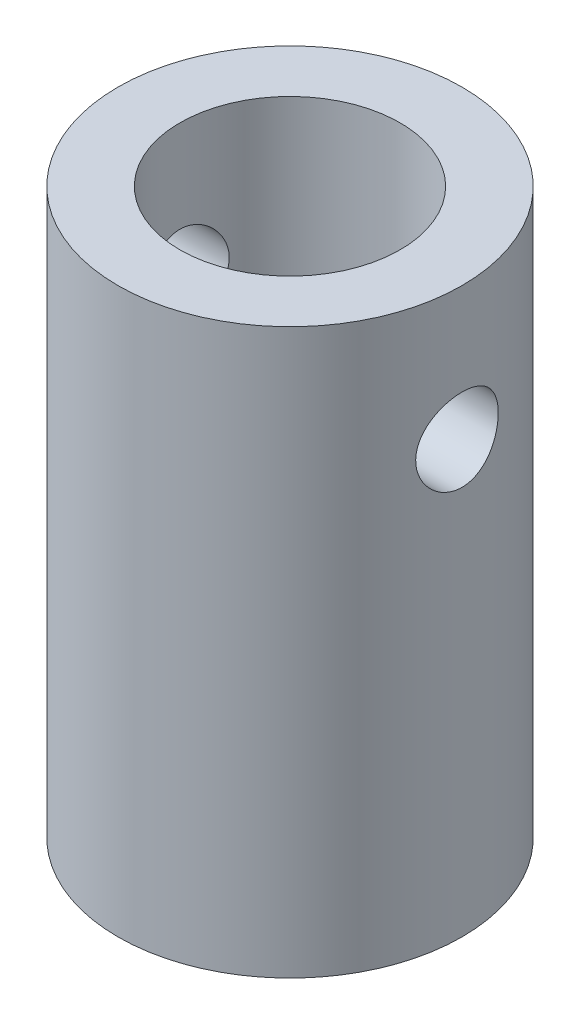
SolidWorks part; units mm, degrees
ref_plane "前视基准面" through (0, 0, 0) normal (0, 0, 1) x (1, 0, 0)
ref_plane "上视基准面" through (0, 0, 0) normal (0, 1, 0) x (1, 0, 0)
ref_plane "右视基准面" through (0, 0, 0) normal (1, 0, 0) x (0, 0, -1)
sketch "草图1" plane through (0, 0, 0) normal (0, 1, 0) x (1, 0, 0)
  circle A0 centre (0, 0) radius 12.5
  arc A1 (1.3201, 7.2813) -> (1.0368, 7.327) centre (0, 0) ccw
  arc A2 (-0.3333, 7.3925) -> (-0.6196, 7.374) centre (0, 0) ccw
  arc A3 (-1.9699, 7.133) -> (-2.2449, 7.0513) centre (0, 0) ccw
  arc A4 (-3.5077, 6.5158) -> (-3.7577, 6.3749) centre (0, 0) ccw
  arc A5 (-4.8697, 5.5719) -> (-5.082, 5.3789) centre (0, 0) ccw
  arc A6 (-5.9875, 4.3486) -> (-6.1516, 4.1132) centre (0, 0) ccw
  arc A7 (-6.805, 2.9072) -> (-6.9126, 2.6412) centre (0, 0) ccw
  arc A8 (-7.2813, 1.3201) -> (-7.327, 1.0368) centre (0, 0) ccw
  arc A9 (-7.3925, -0.3333) -> (-7.374, -0.6196) centre (0, 0) ccw
  arc A10 (-7.133, -1.9699) -> (-7.0513, -2.2449) centre (0, 0) ccw
  arc A11 (-6.5158, -3.5077) -> (-6.3749, -3.7577) centre (0, 0) ccw
  arc A12 (-5.5719, -4.8697) -> (-5.3789, -5.082) centre (0, 0) ccw
  arc A13 (-4.3486, -5.9875) -> (-4.1132, -6.1516) centre (0, 0) ccw
  arc A14 (-2.9072, -6.805) -> (-2.6412, -6.9126) centre (0, 0) ccw
  arc A15 (-1.3201, -7.2813) -> (-1.0368, -7.327) centre (0, 0) ccw
  arc A16 (0.3333, -7.3925) -> (0.6196, -7.374) centre (0, 0) ccw
  arc A17 (1.9699, -7.133) -> (2.2449, -7.0513) centre (0, 0) ccw
  arc A18 (3.5077, -6.5158) -> (3.7577, -6.3749) centre (0, 0) ccw
  arc A19 (4.8697, -5.5719) -> (5.082, -5.3789) centre (0, 0) ccw
  arc A20 (5.9875, -4.3486) -> (6.1516, -4.1132) centre (0, 0) ccw
  arc A21 (6.805, -2.9072) -> (6.9126, -2.6412) centre (0, 0) ccw
  arc A22 (7.2813, -1.3201) -> (7.327, -1.0368) centre (0, 0) ccw
  arc A23 (7.3925, 0.3333) -> (7.374, 0.6196) centre (0, 0) ccw
  arc A24 (7.133, 1.9699) -> (7.0513, 2.2449) centre (0, 0) ccw
  arc A25 (6.5158, 3.5077) -> (6.3749, 3.7577) centre (0, 0) ccw
  arc A26 (5.5719, 4.8697) -> (5.3789, 5.082) centre (0, 0) ccw
  arc A27 (4.3486, 5.9875) -> (4.1132, 6.1516) centre (0, 0) ccw
  arc A28 (2.9072, 6.805) -> (2.6412, 6.9126) centre (0, 0) ccw
  spline S0 degree 3 poles (1.0368, 7.327) (0.9813, 7.2702) (0.9257, 7.2132) (0.8222, 7.0949) (0.7743, 7.0337) (0.6353, 6.8476) (0.5489, 6.72) (0.4775, 6.5871) knots 0 0 0 0 0.25 0.25 0.5 0.5 1 1 1 1
  spline S1 degree 3 poles (0.1466, 6.5886) (0.0874, 6.7295) (0.0225, 6.869) (-0.0958, 7.0714) (-0.1389, 7.1376) (-0.2325, 7.2668) (-0.283, 7.3297) (-0.3333, 7.3925) knots 0 0 0 0 0.5 0.5 0.75 0.75 1 1 1 1
  spline S2 degree 3 poles (-0.6196, 7.374) (-0.661, 7.3063) (-0.7026, 7.2384) (-0.7771, 7.1) (-0.81, 7.0297) (-0.9045, 6.8175) (-0.9618, 6.6745) (-1.0018, 6.5291) knots 0 0 0 0 0.25 0.25 0.5 0.5 1 1 1 1
  spline S3 degree 3 poles (-1.3247, 6.457) (-1.4136, 6.581) (-1.5073, 6.7025) (-1.6673, 6.8732) (-1.724, 6.9281) (-1.8439, 7.033) (-1.907, 7.083) (-1.9699, 7.133) knots 0 0 0 0 0.5 0.5 0.75 0.75 1 1 1 1
  spline S4 degree 3 poles (-2.2449, 7.0513) (-2.2702, 6.9761) (-2.2957, 6.9007) (-2.3374, 6.7494) (-2.3537, 6.6736) (-2.3991, 6.446) (-2.4244, 6.2939) (-2.4311, 6.1434) knots 0 0 0 0 0.25 0.25 0.5 0.5 1 1 1 1
  spline S5 degree 3 poles (-2.7298, 6.0012) (-2.8439, 6.1021) (-2.9619, 6.1997) (-3.1556, 6.3303) (-3.223, 6.3711) (-3.3629, 6.4465) (-3.4355, 6.4812) (-3.5077, 6.5158) knots 0 0 0 0 0.5 0.5 0.75 0.75 1 1 1 1
  spline S6 degree 3 poles (-3.7577, 6.3749) (-3.7657, 6.2961) (-3.7737, 6.2171) (-3.7806, 6.0606) (-3.7796, 5.9832) (-3.7736, 5.7514) (-3.7656, 5.5973) (-3.7387, 5.4493) knots 0 0 0 0 0.25 0.25 0.5 0.5 1 1 1 1
  spline S7 degree 3 poles (-3.9983, 5.2442) (-4.1317, 5.3171) (-4.2683, 5.3857) (-4.4858, 5.4696) (-4.5605, 5.4943) (-4.7134, 5.5366) (-4.7917, 5.5543) (-4.8697, 5.5719) knots 0 0 0 0 0.5 0.5 0.75 0.75 1 1 1 1
  spline S8 degree 3 poles (-5.082, 5.3789) (-5.0723, 5.3005) (-5.0626, 5.2218) (-5.0345, 5.0679) (-5.0162, 4.9928) (-4.9592, 4.7685) (-4.9181, 4.6198) (-4.8591, 4.4817) knots 0 0 0 0 0.25 0.25 0.5 0.5 1 1 1 1
  spline S9 degree 3 poles (-5.0665, 4.2239) (-5.2125, 4.2652) (-5.3608, 4.3013) (-5.5912, 4.3343) (-5.6694, 4.3418) (-5.8275, 4.349) (-5.9076, 4.3488) (-5.9875, 4.3486) knots 0 0 0 0 0.5 0.5 0.75 0.75 1 1 1 1
  spline S10 degree 3 poles (-6.1516, 4.1132) (-6.1247, 4.039) (-6.0978, 3.9646) (-6.0362, 3.8211) (-6.0017, 3.7522) (-5.8966, 3.5463) (-5.8242, 3.4102) (-5.736, 3.289) knots 0 0 0 0 0.25 0.25 0.5 0.5 1 1 1 1
  spline S11 degree 3 poles (-5.8809, 2.9915) (-6.0321, 2.9993) (-6.1847, 3.0007) (-6.4163, 2.9813) (-6.494, 2.9713) (-6.6495, 2.9432) (-6.7273, 2.9251) (-6.805, 2.9072) knots 0 0 0 0 0.5 0.5 0.75 0.75 1 1 1 1
  spline S12 degree 3 poles (-6.9126, 2.6412) (-6.87, 2.575) (-6.8273, 2.5086) (-6.7355, 2.3826) (-6.6866, 2.3232) (-6.5388, 2.1461) (-6.4383, 2.0294) (-6.3256, 1.931) knots 0 0 0 0 0.25 0.25 0.5 0.5 1 1 1 1
  spline S13 degree 3 poles (-6.4007, 1.6088) (-6.5496, 1.5827) (-6.6983, 1.5492) (-6.9194, 1.4784) (-6.9928, 1.4515) (-7.1379, 1.3897) (-7.2097, 1.3548) (-7.2813, 1.3201) knots 0 0 0 0 0.5 0.5 0.75 0.75 1 1 1 1
  spline S14 degree 3 poles (-7.327, 1.0368) (-7.2708, 0.9818) (-7.2145, 0.9267) (-7.0973, 0.8245) (-7.0365, 0.7775) (-6.8533, 0.638) (-6.7297, 0.5467) (-6.5982, 0.476) knots 0 0 0 0 0.25 0.25 0.5 0.5 1 1 1 1
  spline S15 degree 3 poles (-6.5997, 0.1451) (-6.7389, 0.0866) (-6.8759, 0.0197) (-7.0753, -0.0988) (-7.1408, -0.1413) (-7.2684, -0.2336) (-7.3305, -0.2835) (-7.3925, -0.3333) knots 0 0 0 0 0.5 0.5 0.75 0.75 1 1 1 1
  spline S16 degree 3 poles (-7.374, -0.6196) (-7.3071, -0.6606) (-7.2401, -0.7018) (-7.1033, -0.7752) (-7.0338, -0.8075) (-6.8245, -0.9025) (-6.6839, -0.9637) (-6.5402, -1.0033) knots 0 0 0 0 0.25 0.25 0.5 0.5 1 1 1 1
  spline S17 degree 3 poles (-6.468, -1.3262) (-6.5906, -1.4141) (-6.7086, -1.511) (-6.8761, -1.6712) (-6.9305, -1.727) (-7.0343, -1.8452) (-7.0837, -1.9077) (-7.133, -1.9699) knots 0 0 0 0 0.5 0.5 0.75 0.75 1 1 1 1
  spline S18 degree 3 poles (-7.0513, -2.2449) (-6.9771, -2.27) (-6.9026, -2.2952) (-6.7532, -2.3363) (-6.6783, -2.3523) (-6.4535, -2.3982) (-6.3031, -2.426) (-6.1545, -2.4326) knots 0 0 0 0 0.25 0.25 0.5 0.5 1 1 1 1
  spline S19 degree 3 poles (-6.0123, -2.7313) (-6.1121, -2.8442) (-6.2045, -2.9661) (-6.3319, -3.1598) (-6.3725, -3.2261) (-6.4474, -3.3643) (-6.4816, -3.4361) (-6.5158, -3.5077) knots 0 0 0 0 0.5 0.5 0.75 0.75 1 1 1 1
  spline S20 degree 3 poles (-6.3749, -3.7577) (-6.2971, -3.7656) (-6.219, -3.7736) (-6.0644, -3.7805) (-5.9879, -3.7795) (-5.7589, -3.774) (-5.6066, -3.7668) (-5.4604, -3.7402) knots 0 0 0 0 0.25 0.25 0.5 0.5 1 1 1 1
  spline S21 degree 3 poles (-5.2553, -3.9998) (-5.3275, -4.132) (-5.3893, -4.2723) (-5.4699, -4.4897) (-5.4948, -4.5634) (-5.5372, -4.7146) (-5.5545, -4.7923) (-5.5719, -4.8697) knots 0 0 0 0 0.5 0.5 0.75 0.75 1 1 1 1
  spline S22 degree 3 poles (-5.3789, -5.082) (-5.3014, -5.0724) (-5.2236, -5.0628) (-5.0714, -5.0353) (-4.9971, -5.0174) (-4.7754, -4.9609) (-4.6292, -4.9189) (-4.4927, -4.8606) knots 0 0 0 0 0.25 0.25 0.5 0.5 1 1 1 1
  spline S23 degree 3 poles (-4.235, -5.068) (-4.276, -5.2131) (-4.3037, -5.3642) (-4.3335, -5.5943) (-4.3416, -5.6716) (-4.3493, -5.8285) (-4.3489, -5.9081) (-4.3486, -5.9875) knots 0 0 0 0 0.5 0.5 0.75 0.75 1 1 1 1
  spline S24 degree 3 poles (-4.1132, -6.1516) (-4.0398, -6.1249) (-3.9661, -6.0982) (-3.8239, -6.0376) (-3.7554, -6.0037) (-3.5522, -5.8991) (-3.42, -5.8247) (-3.3, -5.7375) knots 0 0 0 0 0.25 0.25 0.5 0.5 1 1 1 1
  spline S25 degree 3 poles (-3.0026, -5.8824) (-3.0103, -6.0331) (-3.0024, -6.1869) (-2.9799, -6.4181) (-2.9707, -6.4953) (-2.9434, -6.6501) (-2.9252, -6.7277) (-2.9072, -6.805) knots 0 0 0 0 0.5 0.5 0.75 0.75 1 1 1 1
  spline S26 degree 3 poles (-2.6412, -6.9126) (-2.5756, -6.8703) (-2.5097, -6.8279) (-2.3845, -6.7372) (-2.3251, -6.689) (-2.1506, -6.5415) (-2.0396, -6.4388) (-1.9421, -6.3271) knots 0 0 0 0 0.25 0.25 0.5 0.5 1 1 1 1
  spline S27 degree 3 poles (-1.6199, -6.4022) (-1.5938, -6.5509) (-1.5508, -6.6993) (-1.477, -6.9199) (-1.4509, -6.9932) (-1.3899, -7.1382) (-1.3549, -7.2098) (-1.3201, -7.2813) knots 0 0 0 0 0.5 0.5 0.75 0.75 1 1 1 1
  spline S28 degree 3 poles (-1.0368, -7.327) (-0.9823, -7.2711) (-0.9275, -7.2151) (-0.8256, -7.099) (-0.7783, -7.0389) (-0.6413, -6.856) (-0.5572, -6.7303) (-0.487, -6.5997) knots 0 0 0 0 0.25 0.25 0.5 0.5 1 1 1 1
  spline S29 degree 3 poles (-0.1562, -6.6012) (-0.0976, -6.7406) (-0.0218, -6.8757) (0.0996, -7.0746) (0.1414, -7.1403) (0.2332, -7.2683) (0.2833, -7.3305) (0.3333, -7.3925) knots 0 0 0 0 0.5 0.5 0.75 0.75 1 1 1 1
  spline S30 degree 3 poles (0.6196, -7.374) (0.6604, -7.3073) (0.7013, -7.2404) (0.7751, -7.1042) (0.8079, -7.035) (0.9004, -6.8261) (0.9528, -6.6847) (0.9922, -6.5417) knots 0 0 0 0 0.25 0.25 0.5 0.5 1 1 1 1
  spline S31 degree 3 poles (1.3151, -6.4695) (1.4034, -6.5927) (1.5079, -6.7074) (1.6709, -6.8745) (1.7263, -6.9295) (1.8445, -7.034) (1.9073, -7.0836) (1.9699, -7.133) knots 0 0 0 0 0.5 0.5 0.75 0.75 1 1 1 1
  spline S32 degree 3 poles (2.2449, -7.0513) (2.2699, -6.9771) (2.2949, -6.9027) (2.3366, -6.7533) (2.3534, -6.6784) (2.3966, -6.4539) (2.4149, -6.3044) (2.4215, -6.156) knots 0 0 0 0 0.25 0.25 0.5 0.5 1 1 1 1
  spline S33 degree 3 poles (2.7202, -6.0138) (2.834, -6.1144) (2.9617, -6.2031) (3.1582, -6.33) (3.2245, -6.3713) (3.3632, -6.4471) (3.4356, -6.4815) (3.5077, -6.5158) knots 0 0 0 0 0.5 0.5 0.75 0.75 1 1 1 1
  spline S34 degree 3 poles (3.7577, -6.3749) (3.7655, -6.2969) (3.7733, -6.2187) (3.7809, -6.0635) (3.7806, -5.9867) (3.7724, -5.7579) (3.7557, -5.6082) (3.7291, -5.4619) knots 0 0 0 0 0.25 0.25 0.5 0.5 1 1 1 1
  spline S35 degree 3 poles (3.9887, -5.2568) (4.1222, -5.3297) (4.2667, -5.388) (4.4868, -5.4683) (4.5608, -5.4939) (4.7132, -5.537) (4.7916, -5.5544) (4.8697, -5.5719) knots 0 0 0 0 0.5 0.5 0.75 0.75 1 1 1 1
  spline S36 degree 3 poles (5.082, -5.3789) (5.0722, -5.301) (5.0624, -5.2229) (5.0353, -5.0696) (5.0179, -4.9946) (4.9586, -4.7732) (4.9081, -4.6312) (4.8495, -4.4942) knots 0 0 0 0 0.25 0.25 0.5 0.5 1 1 1 1
  spline S37 degree 3 poles (5.0569, -4.2365) (5.2036, -4.278) (5.3575, -4.3032) (5.5903, -4.3328) (5.6684, -4.3413) (5.8268, -4.3494) (5.9073, -4.3489) (5.9875, -4.3486) knots 0 0 0 0 0.5 0.5 0.75 0.75 1 1 1 1
  spline S38 degree 3 poles (6.1516, -4.1132) (6.1246, -4.0393) (6.0976, -3.9652) (6.0369, -3.8215) (6.0033, -3.752) (5.8957, -3.5492) (5.8142, -3.4223) (5.7265, -3.3015) knots 0 0 0 0 0.25 0.25 0.5 0.5 1 1 1 1
  spline S39 degree 3 poles (5.8714, -3.0041) (6.0238, -3.0119) (6.1796, -3.0031) (6.4136, -2.9804) (6.4917, -2.9712) (6.6483, -2.9438) (6.7268, -2.9254) (6.805, -2.9072) knots 0 0 0 0 0.5 0.5 0.75 0.75 1 1 1 1
  spline S40 degree 3 poles (6.9126, -2.6412) (6.8698, -2.5751) (6.8269, -2.5087) (6.7355, -2.3818) (6.6872, -2.3215) (6.5368, -2.1475) (6.4287, -2.042) (6.316, -1.9436) knots 0 0 0 0 0.25 0.25 0.5 0.5 1 1 1 1
  spline S41 degree 3 poles (6.3911, -1.6214) (6.5417, -1.595) (6.6919, -1.5527) (6.9154, -1.4788) (6.9896, -1.4524) (7.1364, -1.3907) (7.2089, -1.3553) (7.2813, -1.3201) knots 0 0 0 0 0.5 0.5 0.75 0.75 1 1 1 1
  spline S42 degree 3 poles (7.327, -1.0368) (7.2705, -0.9815) (7.2138, -0.9261) (7.0961, -0.8234) (7.0353, -0.7758) (6.9121, -0.6832) (6.8498, -0.6381) (6.7212, -0.5577) (6.6552, -0.5221) (6.5886, -0.4885) knots 0 0 0 0 0.25 0.25 0.5 0.5 0.75 0.75 1 1 1 1
  spline S43 degree 3 poles (6.5901, -0.1577) (6.7316, -0.0999) (6.869, -0.0256) (7.0705, 0.097) (7.1371, 0.1392) (7.2668, 0.232) (7.3297, 0.2827) (7.3925, 0.3333) knots 0 0 0 0 0.5 0.5 0.75 0.75 1 1 1 1
  spline S44 degree 3 poles (7.374, 0.6196) (7.3065, 0.661) (7.2387, 0.7025) (7.1006, 0.7767) (7.0304, 0.8093) (6.8189, 0.9046) (6.6764, 0.9634) (6.5306, 0.9907) knots 0 0 0 0 0.25 0.25 0.5 0.5 1 1 1 1
  spline S45 degree 3 poles (6.4585, 1.3136) (6.583, 1.403) (6.7015, 1.5041) (6.8717, 1.6671) (6.9271, 1.7234) (7.0327, 1.8432) (7.0829, 1.9067) (7.133, 1.9699) knots 0 0 0 0 0.5 0.5 0.75 0.75 1 1 1 1
  spline S46 degree 3 poles (7.0513, 2.2449) (6.9761, 2.2701) (6.9008, 2.2954) (6.7495, 2.3377) (6.6737, 2.3548) (6.4464, 2.3973) (6.2952, 2.4133) (6.1449, 2.42) knots 0 0 0 0 0.25 0.25 0.5 0.5 1 1 1 1
  spline S47 degree 3 poles (6.0027, 2.7188) (6.1043, 2.8336) (6.1983, 2.9576) (6.3284, 3.154) (6.3699, 3.2214) (6.4462, 3.3619) (6.481, 3.4349) (6.5158, 3.5077) knots 0 0 0 0 0.5 0.5 0.75 0.75 1 1 1 1
  spline S48 degree 3 poles (6.3749, 3.7577) (6.296, 3.7655) (6.2168, 3.7735) (6.0597, 3.781) (5.9819, 3.7807) (5.7505, 3.7717) (5.599, 3.7546) (5.4508, 3.7276) knots 0 0 0 0 0.25 0.25 0.5 0.5 1 1 1 1
  spline S49 degree 3 poles (5.2457, 3.9872) (5.3192, 4.1218) (5.3845, 4.2628) (5.468, 4.483) (5.4934, 4.558) (5.5364, 4.712) (5.5542, 4.791) (5.5719, 4.8697) knots 0 0 0 0 0.5 0.5 0.75 0.75 1 1 1 1
  spline S50 degree 3 poles (5.3789, 5.082) (5.3001, 5.0721) (5.2211, 5.0622) (5.0662, 5.0345) (4.9904, 5.0168) (4.7664, 4.9568) (4.6218, 4.9073) (4.4832, 4.848) knots 0 0 0 0 0.25 0.25 0.5 0.5 1 1 1 1
  spline S51 degree 3 poles (4.2254, 5.0554) (4.2671, 5.203) (4.3006, 5.3543) (4.3336, 5.5873) (4.3415, 5.6661) (4.3491, 5.8258) (4.3488, 5.9068) (4.3486, 5.9875) knots 0 0 0 0 0.5 0.5 0.75 0.75 1 1 1 1
  spline S52 degree 3 poles (4.1132, 6.1516) (4.0385, 6.1243) (3.9636, 6.0971) (3.8187, 6.0355) (3.7489, 6.0013) (3.5435, 5.8932) (3.4125, 5.8137) (3.2905, 5.725) knots 0 0 0 0 0.25 0.25 0.5 0.5 1 1 1 1
  spline S53 degree 3 poles (2.993, 5.8699) (3.0009, 6.0229) (3.001, 6.1775) (2.9817, 6.4118) (2.9718, 6.4903) (2.9436, 6.6476) (2.9253, 6.7264) (2.9072, 6.805) knots 0 0 0 0 0.5 0.5 0.75 0.75 1 1 1 1
  spline S54 degree 3 poles (2.6412, 6.9126) (2.5745, 6.8695) (2.5075, 6.8263) (2.38, 6.7339) (2.3196, 6.6849) (2.143, 6.534) (2.0318, 6.4282) (1.9325, 6.3145) knots 0 0 0 0 0.25 0.25 0.5 0.5 1 1 1 1
  spline S55 degree 3 poles (1.6103, 6.3896) (1.5839, 6.5404) (1.5508, 6.691) (1.4802, 6.9149) (1.453, 6.9892) (1.3905, 7.1361) (1.3552, 7.2088) (1.3201, 7.2813) knots 0 0 0 0 0.5 0.5 0.75 0.75 1 1 1 1
  spline S56 degree 3 poles (0.4775, 6.5871) (0.4657, 6.56) (0.447, 6.5346) (0.3926, 6.4942) (0.3549, 6.4794) (0.2744, 6.4783) (0.2342, 6.4929) (0.1775, 6.5346) (0.1584, 6.5609) (0.1466, 6.5886) knots 0 0 0 0 0.25 0.25 0.5 0.5 0.75 0.75 1 1 1 1
  spline S57 degree 3 poles (-1.0018, 6.5291) (-1.0073, 6.5001) (-1.0199, 6.4712) (-1.0639, 6.4196) (-1.0973, 6.3968) (-1.1756, 6.3779) (-1.218, 6.3832) (-1.2826, 6.4111) (-1.3071, 6.4326) (-1.3247, 6.457) knots 0 0 0 0 0.25 0.25 0.5 0.5 0.75 0.75 1 1 1 1
  spline S58 degree 3 poles (-2.4311, 6.1434) (-2.4299, 6.1139) (-2.4358, 6.0829) (-2.4672, 6.0228) (-2.4947, 5.9931) (-2.5668, 5.9573) (-2.6094, 5.953) (-2.6785, 5.9659) (-2.7072, 5.9813) (-2.7298, 6.0012) knots 0 0 0 0 0.25 0.25 0.5 0.5 0.75 0.75 1 1 1 1
  spline S59 degree 3 poles (-3.7387, 5.4493) (-3.731, 5.4208) (-3.7298, 5.3893) (-3.7471, 5.3237) (-3.7673, 5.2887) (-3.8296, 5.2377) (-3.8702, 5.224) (-3.9404, 5.2212) (-3.9718, 5.2299) (-3.9983, 5.2442) knots 0 0 0 0 0.25 0.25 0.5 0.5 0.75 0.75 1 1 1 1
  spline S60 degree 3 poles (-4.8591, 4.4817) (-4.8452, 4.4555) (-4.837, 4.4251) (-4.8393, 4.3573) (-4.8512, 4.3187) (-4.9006, 4.2551) (-4.9371, 4.2327) (-5.005, 4.2144) (-5.0375, 4.2158) (-5.0665, 4.2239) knots 0 0 0 0 0.25 0.25 0.5 0.5 0.75 0.75 1 1 1 1
  spline S61 degree 3 poles (-5.736, 3.289) (-5.7167, 3.2666) (-5.7019, 3.2387) (-5.6891, 3.1722) (-5.6921, 3.1318) (-5.7261, 3.0588) (-5.7567, 3.0289) (-5.8188, 2.9959) (-5.8508, 2.9901) (-5.8809, 2.9915) knots 0 0 0 0 0.25 0.25 0.5 0.5 0.75 0.75 1 1 1 1
  spline S62 degree 3 poles (-6.3256, 1.931) (-6.3017, 1.9135) (-6.2812, 1.8896) (-6.2538, 1.8276) (-6.2478, 1.7876) (-6.2647, 1.7088) (-6.2879, 1.6729) (-6.3411, 1.6269) (-6.371, 1.6141) (-6.4007, 1.6088) knots 0 0 0 0 0.25 0.25 0.5 0.5 0.75 0.75 1 1 1 1
  spline S63 degree 3 poles (-6.5982, 0.476) (-6.5716, 0.4636) (-6.5469, 0.4446) (-6.5075, 0.3902) (-6.4933, 0.3528) (-6.4923, 0.2735) (-6.5062, 0.2338) (-6.5468, 0.1769) (-6.5725, 0.1574) (-6.5997, 0.1451) knots 0 0 0 0 0.25 0.25 0.5 0.5 0.75 0.75 1 1 1 1
  spline S64 degree 3 poles (-6.5402, -1.0033) (-6.5113, -1.0091) (-6.4827, -1.0219) (-6.4318, -1.0661) (-6.4093, -1.0994) (-6.3905, -1.1771) (-6.3955, -1.2192) (-6.4229, -1.2837) (-6.444, -1.3083) (-6.468, -1.3262) knots 0 0 0 0 0.25 0.25 0.5 0.5 0.75 0.75 1 1 1 1
  spline S65 degree 3 poles (-6.1545, -2.4326) (-6.125, -2.4315) (-6.0941, -2.4375) (-6.0342, -2.469) (-6.0046, -2.4965) (-5.9688, -2.5684) (-5.9645, -2.6109) (-5.9772, -2.68) (-5.9925, -2.7087) (-6.0123, -2.7313) knots 0 0 0 0 0.25 0.25 0.5 0.5 0.75 0.75 1 1 1 1
  spline S66 degree 3 poles (-5.4604, -3.7402) (-5.4318, -3.7324) (-5.4003, -3.7312) (-5.3347, -3.7484) (-5.2996, -3.7686) (-5.2485, -3.831) (-5.2349, -3.8716) (-5.2321, -3.9419) (-5.2409, -3.9733) (-5.2553, -3.9998) knots 0 0 0 0 0.25 0.25 0.5 0.5 0.75 0.75 1 1 1 1
  spline S67 degree 3 poles (-4.4927, -4.8606) (-4.4666, -4.8465) (-4.4362, -4.8382) (-4.3683, -4.8403) (-4.3295, -4.8522) (-4.2657, -4.9017) (-4.2434, -4.9383) (-4.2252, -5.0064) (-4.2268, -5.039) (-4.235, -5.068) knots 0 0 0 0 0.25 0.25 0.5 0.5 0.75 0.75 1 1 1 1
  spline S68 degree 3 poles (-3.3, -5.7375) (-3.2777, -5.7181) (-3.2498, -5.7032) (-3.1832, -5.6902) (-3.1428, -5.6931) (-3.0696, -5.7272) (-3.0397, -5.7579) (-3.0067, -5.8202) (-3.001, -5.8523) (-3.0026, -5.8824) knots 0 0 0 0 0.25 0.25 0.5 0.5 0.75 0.75 1 1 1 1
  spline S69 degree 3 poles (-1.9421, -6.3271) (-1.9246, -6.3033) (-1.9007, -6.2827) (-1.8387, -6.2554) (-1.7987, -6.2493) (-1.72, -6.2662) (-1.684, -6.2893) (-1.638, -6.3426) (-1.6252, -6.3725) (-1.6199, -6.4022) knots 0 0 0 0 0.25 0.25 0.5 0.5 0.75 0.75 1 1 1 1
  spline S70 degree 3 poles (-0.487, -6.5997) (-0.4751, -6.5727) (-0.4563, -6.5476) (-0.4019, -6.5074) (-0.3644, -6.4928) (-0.2843, -6.4917) (-0.2441, -6.5061) (-0.1873, -6.5474) (-0.1681, -6.5736) (-0.1562, -6.6012) knots 0 0 0 0 0.25 0.25 0.5 0.5 0.75 0.75 1 1 1 1
  spline S71 degree 3 poles (0.9922, -6.5417) (0.9977, -6.5126) (1.0103, -6.4837) (1.0543, -6.4322) (1.0876, -6.4094) (1.1659, -6.3904) (1.2084, -6.3957) (1.273, -6.4237) (1.2975, -6.4451) (1.3151, -6.4695) knots 0 0 0 0 0.25 0.25 0.5 0.5 0.75 0.75 1 1 1 1
  spline S72 degree 3 poles (2.4215, -6.156) (2.4204, -6.1264) (2.4261, -6.0958) (2.4577, -6.0353) (2.4851, -6.0057) (2.5574, -5.9698) (2.5995, -5.9655) (2.669, -5.9784) (2.6976, -5.9939) (2.7202, -6.0138) knots 0 0 0 0 0.25 0.25 0.5 0.5 0.75 0.75 1 1 1 1
  spline S73 degree 3 poles (3.7291, -5.4619) (3.7214, -5.4333) (3.7202, -5.4018) (3.7375, -5.3364) (3.7577, -5.3013) (3.82, -5.2503) (3.8605, -5.2366) (3.9308, -5.2337) (3.9622, -5.2424) (3.9887, -5.2568) knots 0 0 0 0 0.25 0.25 0.5 0.5 0.75 0.75 1 1 1 1
  spline S74 degree 3 poles (4.8495, -4.4942) (4.8356, -4.4681) (4.8274, -4.4378) (4.8298, -4.3696) (4.8414, -4.3315) (4.8916, -4.267) (4.9276, -4.2453) (4.9954, -4.2269) (5.028, -4.2284) (5.0569, -4.2365) knots 0 0 0 0 0.25 0.25 0.5 0.5 0.75 0.75 1 1 1 1
  spline S75 degree 3 poles (5.7265, -3.3015) (5.7071, -3.2791) (5.6924, -3.2513) (5.6795, -3.1848) (5.6826, -3.1442) (5.7167, -3.0712) (5.7469, -3.0416) (5.8094, -3.0084) (5.8413, -3.0027) (5.8714, -3.0041) knots 0 0 0 0 0.25 0.25 0.5 0.5 0.75 0.75 1 1 1 1
  spline S76 degree 3 poles (6.316, -1.9436) (6.2922, -1.9261) (6.2717, -1.9022) (6.2443, -1.8403) (6.2382, -1.8001) (6.2552, -1.7213) (6.2781, -1.6856) (6.3316, -1.6393) (6.3615, -1.6267) (6.3911, -1.6214) knots 0 0 0 0 0.25 0.25 0.5 0.5 0.75 0.75 1 1 1 1
  spline S77 degree 3 poles (6.5886, -0.4885) (6.5615, -0.4767) (6.5362, -0.458) (6.4957, -0.4037) (6.4809, -0.3663) (6.4798, -0.2851) (6.4942, -0.2456) (6.5362, -0.1883) (6.5624, -0.1694) (6.5901, -0.1577) knots 0 0 0 0 0.25 0.25 0.5 0.5 0.75 0.75 1 1 1 1
  spline S78 degree 3 poles (6.5306, 0.9907) (6.5015, 0.9962) (6.4726, 1.0088) (6.4211, 1.0529) (6.3983, 1.0863) (6.3794, 1.1647) (6.3845, 1.2065) (6.4127, 1.2718) (6.4341, 1.296) (6.4585, 1.3136) knots 0 0 0 0 0.25 0.25 0.5 0.5 0.75 0.75 1 1 1 1
  spline S79 degree 3 poles (6.1449, 2.42) (6.1154, 2.4189) (6.0844, 2.4247) (6.0244, 2.4562) (5.9947, 2.4836) (5.9588, 2.5558) (5.9545, 2.5983) (5.9674, 2.6675) (5.9828, 2.6961) (6.0027, 2.7188) knots 0 0 0 0 0.25 0.25 0.5 0.5 0.75 0.75 1 1 1 1
  spline S80 degree 3 poles (5.4508, 3.7276) (5.4223, 3.7199) (5.3908, 3.7187) (5.3253, 3.736) (5.2902, 3.7562) (5.2392, 3.8185) (5.2255, 3.8589) (5.2227, 3.9296) (5.2314, 3.9607) (5.2457, 3.9872) knots 0 0 0 0 0.25 0.25 0.5 0.5 0.75 0.75 1 1 1 1
  spline S81 degree 3 poles (4.4832, 4.848) (4.4571, 4.8341) (4.4267, 4.826) (4.359, 4.8282) (4.3204, 4.8401) (4.2568, 4.8893) (4.2344, 4.9258) (4.2159, 4.9937) (4.2173, 5.0264) (4.2254, 5.0554) knots 0 0 0 0 0.25 0.25 0.5 0.5 0.75 0.75 1 1 1 1
  spline S82 degree 3 poles (3.2905, 5.725) (3.2681, 5.7056) (3.2402, 5.6909) (3.1737, 5.678) (3.1334, 5.681) (3.0604, 5.715) (3.0304, 5.7456) (2.9974, 5.8077) (2.9916, 5.8398) (2.993, 5.8699) knots 0 0 0 0 0.25 0.25 0.5 0.5 0.75 0.75 1 1 1 1
  spline S83 degree 3 poles (1.9325, 6.3145) (1.915, 6.2907) (1.8911, 6.2701) (1.8291, 6.2428) (1.7891, 6.2367) (1.7104, 6.2536) (1.6744, 6.2768) (1.6284, 6.33) (1.6156, 6.36) (1.6103, 6.3896) knots 0 0 0 0 0.25 0.25 0.5 0.5 0.75 0.75 1 1 1 1
extrude "凸台-拉伸1" add sketch "草图1" along normal blind 41
ref_plane "基准面1" through (0, 41, 0) normal (0, 1, 0) x (1, 0, 0)
sketch "草图2" plane through (0, 41, 0) normal (0, 1, 0) x (1, 0, 0)
  circle A0 centre (0, 0) radius 8
extrude "切除-拉伸1" cut sketch "草图2" against normal blind 19
sketch "草图4" plane through (0, 0, 0) normal (1, 0, 0) x (0, 0, -1)
  line L0 (0, 13.75) -> (0, -13.75) construction
  line L1 (12.5, 41) -> (-12.5, 41) construction
  circle A0 centre (0, 31.3) radius 3
  dimension "D1" = 9.7
extrude "切除-拉伸2" cut sketch "草图4" against normal through all both and the other way through all
